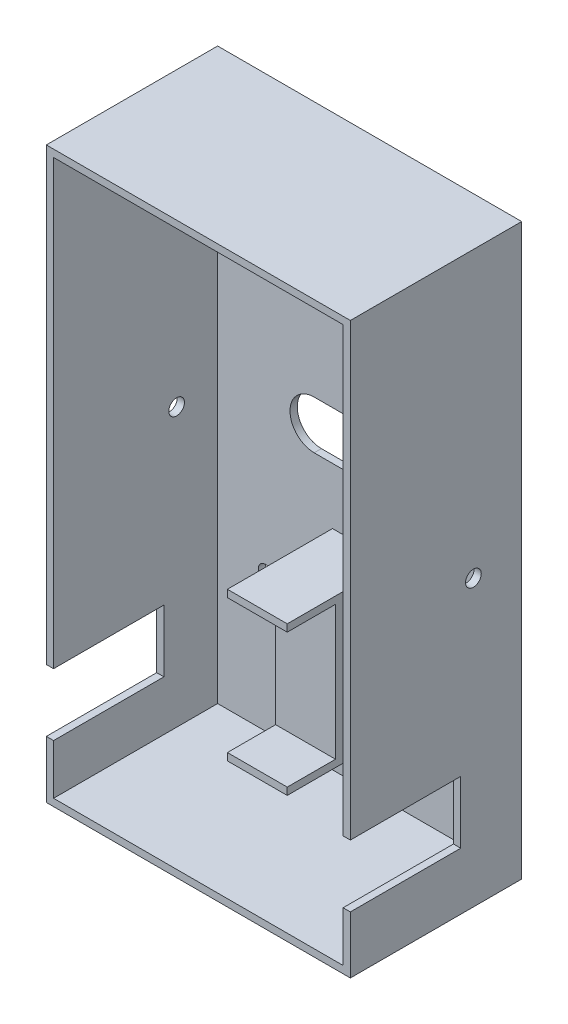
SolidWorks part; units mm, degrees
ref_plane "Front Plane" through (0, 0, 0) normal (0, 0, 1) x (1, 0, 0)
ref_plane "Top Plane" through (0, 0, 0) normal (0, 1, 0) x (1, 0, 0)
ref_plane "Right Plane" through (0, 0, 0) normal (1, 0, 0) x (0, 0, -1)
ref_plane "Plane1" through (0, 0, 34) normal (0, 0, 1) x (1, 0, 0)
sketch "Sketch1" plane through (0, 0, 34) normal (0, 0, 1) x (1, 0, 0)
  line L0 (-1.5, -1.5) -> (61.5, -1.5)
  line L1 (61.5, -1.5) -> (61.5, 116.5)
  line L2 (61.5, 116.5) -> (-1.5, 116.5)
  line L3 (-1.5, 116.5) -> (-1.5, -1.5)
extrude "Boss-Extrude1" add sketch "Sketch1" against normal blind 35.5
sketch "Sketch2" plane through (0, 0, 34) normal (0, 0, 1) x (1, 0, 0)
  line L0 (0, 115) -> (0, 0)
  line L1 (0, 0) -> (60, 0)
  line L2 (60, 0) -> (60, 115)
  line L3 (60, 115) -> (0, 115)
extrude "Cut-Extrude1" cut sketch "Sketch2" against normal blind 34
sketch "Sketch3" plane through (0, 0, 0) normal (0, 0, 1) x (1, 0, 0)
  line L0 (36.2, 43.3) -> (36.2, 12.5)
  line L1 (36.2, 12.5) -> (23.8, 12.5)
  line L2 (23.8, 12.5) -> (23.8, 43.3)
  line L3 (23.8, 43.3) -> (36.2, 43.3)
extrude "Boss-Extrude2" add sketch "Sketch3" along normal blind 21.78
sketch "Sketch4" plane through (23.8, 0, 0) normal (-1, 0, 0) x (0, 0, 1)
  line L0 (21.78, 14) -> (21.78, 41.8)
  line L1 (21.78, 41.8) -> (11.78, 41.8)
  line L2 (11.78, 41.8) -> (11.78, 14)
  line L3 (11.78, 14) -> (21.78, 14)
extrude "Cut-Extrude2" cut sketch "Sketch4" against normal up to next
sketch "Sketch5" plane through (61.5, 0, 0) normal (1, 0, 0) x (0, 0, -1)
  line L0 (-34, 23.25) -> (-34, 10.36)
  line L1 (-34, 10.36) -> (-11.13, 10.36)
  line L2 (-11.13, 10.36) -> (-11.13, 23.25)
  line L3 (-11.13, 23.25) -> (-34, 23.25)
extrude "Cut-Extrude3" cut sketch "Sketch5" against normal up to next
sketch "Sketch6" plane through (-1.5, 0, 0) normal (-1, 0, 0) x (0, 0, 1)
  line L0 (34, 10.36) -> (34, 23.25)
  line L1 (34, 23.25) -> (11.13, 23.25)
  line L2 (11.13, 23.25) -> (11.13, 10.36)
  line L3 (11.13, 10.36) -> (34, 10.36)
extrude "Cut-Extrude4" cut sketch "Sketch6" against normal up to next
sketch "Sketch7" plane through (0, 0, -1.5) normal (0, 0, -1) x (-1, 0, 0)
  line L0 (-40, 55) -> (-20, 55)
  line L1 (-20, 65) -> (-40, 65)
  arc A0 (-20, 55) -> (-20, 65) centre (-20, 60) ccw
  arc A1 (-40, 65) -> (-40, 55) centre (-40, 60) ccw
extrude "Cut-Extrude5" cut sketch "Sketch7" against normal through all
hole_wizard "M2.5 Clearance Hole1" positions "Sketch9" profile "Sketch8" hole size "M2.5" standard "ANSI Metric"
sketch "Sketch9" plane through (0, 0, -1.5) normal (0, 0, -1) x (-1, 0, 0)
  point P0 (-9.95, 28.42)
  point P1 (-9.95, 21.935)
  point P2 (-50.05, 28.42)
  point P3 (-50.05, 21.935)
sketch "Sketch8" plane through (9.95, 28.42, -1.5) normal (1, 0, 0) x (0, 1, 0)
  line L0 (0, 0) -> (0, 35.5)
  line L1 (0, 35.5) -> (1.525, 35.5)
  line L2 (1.525, 35.5) -> (1.525, 0)
  line L5 (1.525, 0) -> (0, 0)
  line L11 (0, -6.35) -> (0, 107.95) construction
  dimension "Thru Hole Dia." = 3.05
  dimension "Thru Hole Depth" = 35.5
hole_wizard "M3 Clearance Hole1" positions "Sketch11" profile "Sketch10" hole size "M3" standard "ANSI Metric"
sketch "Sketch11" plane through (0, 0, 0) normal (1, 0, 0) x (0, 0, -1)
  point P0 (-8.5, 57.5)
sketch "Sketch10" plane through (0, 57.5, 8.5) normal (0, 1, 0) x (0, 0, -1)
  line L0 (0, 0) -> (0, 1.5)
  line L1 (0, 1.5) -> (1.6256, 1.5)
  line L2 (1.6256, 1.5) -> (1.6256, 0)
  line L5 (1.6256, 0) -> (0, 0)
  line L11 (0, -6.35) -> (0, 107.95) construction
  dimension "Thru Hole Dia." = 3.2512
  dimension "Thru Hole Depth" = 1.5
hole_wizard "M3 Clearance Hole2" positions "Sketch13" profile "Sketch12" hole size "M3" standard "ANSI Metric"
sketch "Sketch13" plane through (61.5, 0, 0) normal (1, 0, 0) x (0, 0, -1)
  point P0 (-8.5, 57.5)
sketch "Sketch12" plane through (61.5, 57.5, 8.5) normal (0, 1, 0) x (0, 0, -1)
  line L0 (0, 0) -> (0, 63)
  line L1 (0, 63) -> (1.6256, 63)
  line L2 (1.6256, 63) -> (1.6256, 0)
  line L5 (1.6256, 0) -> (0, 0)
  line L11 (0, -6.35) -> (0, 107.95) construction
  dimension "Thru Hole Dia." = 3.2512
  dimension "Thru Hole Depth" = 63
ref_plane "Plane2" through (0, 0, 34) normal (0, 0, 1) x (1, 0, 0)
